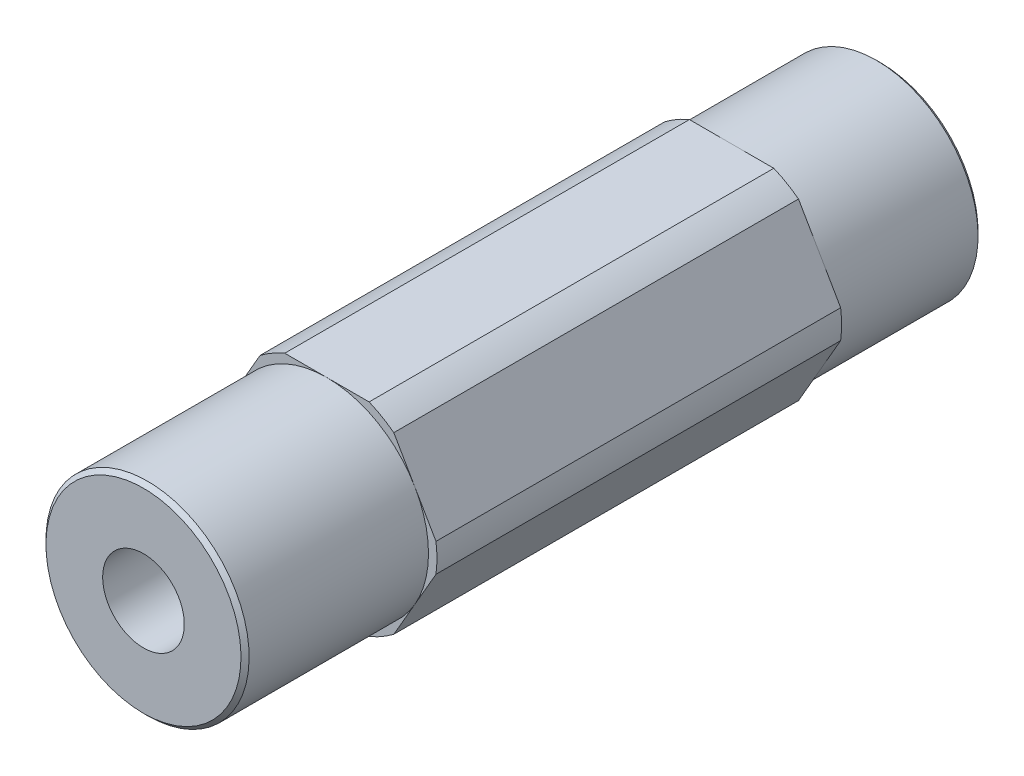
SolidWorks part; units mm, degrees
material "6061-T6 (SS)"
ref_plane "Front Plane" through (0, 0, 0) normal (0, 0, 1) x (1, 0, 0)
ref_plane "Top Plane" through (0, 0, 0) normal (0, 1, 0) x (1, 0, 0)
ref_plane "Right Plane" through (0, 0, 0) normal (1, 0, 0) x (0, 0, -1)
sketch "Sketch1" plane through (0, 0, 0) normal (1, 0, 0) x (0, 0, -1)
  line L0 (29.5405, 0) -> (-46.0756, 0) construction
  line L1 (0, 0) -> (-46.0756, 0)
  line L2 (0, 0) -> (0, 6.35)
  line L3 (-34.6075, 6.8758) -> (-9.3091, 6.8758)
  line L4 (-34.6075, 6.8758) -> (-34.6075, 6.35)
  line L5 (-9.3091, 6.8758) -> (-9.3091, 6.35)
  line L6 (-9.3091, 6.35) -> (0, 6.35)
  line L9 (-46.0756, 6.35) -> (-34.6075, 6.35)
  line L10 (-46.0756, 6.35) -> (-46.0756, 0)
  dimension "D1" = 12.7
  dimension "D2" = 13.7516
  dimension "D3" = 9.3091
  dimension "D4" = 25.2984
  dimension "D5" = 12.7
  dimension "D7" = 11.4681
revolve "Revolve1" add sketch "Sketch1" angle 360 about L0
sketch "Sketch2" plane through (0, 0, 0) normal (0, 0, -1) x (-1, 0, 0)
  line L1 (3.6662, -6.35) -> (7.3323, 0)
  line L2 (7.3323, 0) -> (3.6662, 6.35)
  line L3 (3.6662, 6.35) -> (-3.6662, 6.35)
  line L4 (-3.6662, 6.35) -> (-7.3323, 0)
  line L5 (-7.3323, 0) -> (-3.6662, -6.35)
  line L6 (-3.6662, -6.35) -> (3.6662, -6.35)
  circle A0 centre (0, 0) radius 6.35 construction
  circle A1 centre (0, 0) radius 2.5527
  dimension "D1" = 12.7
  dimension "D2" = 5.1054
extrude "Cut-Extrude3" cut sketch "Sketch2" against normal through all flip side to cut
chamfer "Chamfer1" distance 0.254 angle 45 2 edges at (0, 6.35, 0) (0, 6.35, 46.0756)
